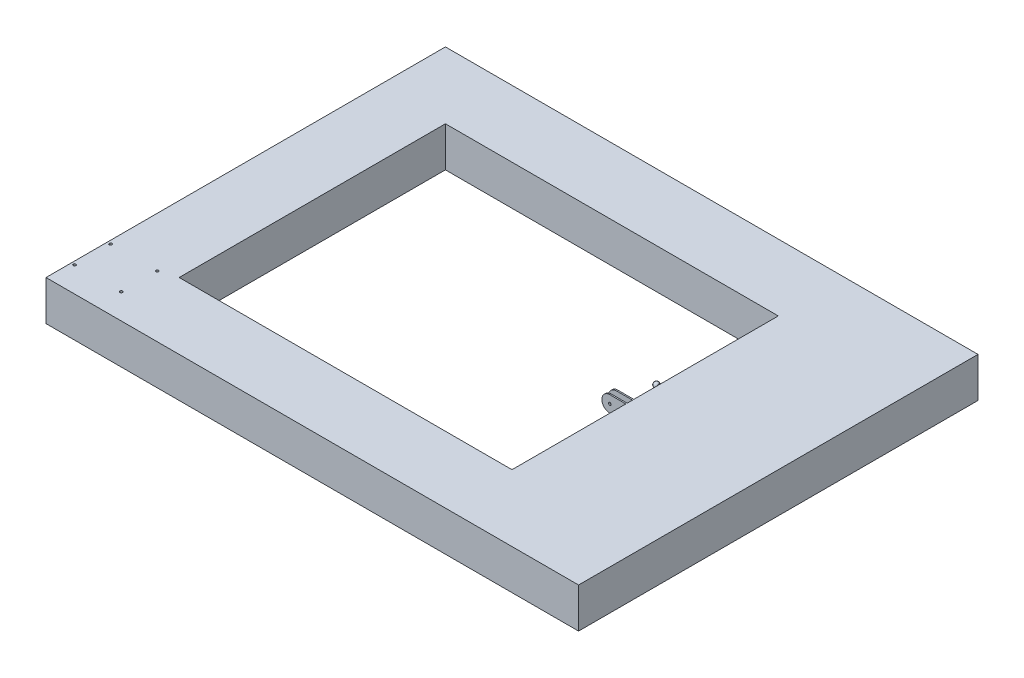
SolidWorks part; units mm, degrees
ref_plane "Front Plane" through (0, 0, 0) normal (0, 0, 1) x (1, 0, 0)
ref_plane "Top Plane" through (0, 0, 0) normal (0, 1, 0) x (1, 0, 0)
ref_plane "Right Plane" through (0, 0, 0) normal (1, 0, 0) x (0, 0, -1)
sketch "Sketch1" plane through (0, 0, 0) normal (0, 0, 1) x (1, 0, 0)
  line L1 (0, 0) -> (4000, 0)
  line L2 (0, 0) -> (0, 300)
  line L3 (0, 300) -> (4000, 300)
  line L4 (4000, 0) -> (4000, 300)
  dimension "D1" = 4000
  dimension "D2" = 300
extrude "Boss-Extrude1" add sketch "Sketch1" along normal blind 3000
sketch "Sketch3" plane through (0, 300, 0) normal (0, 1, 0) x (1, 0, 0)
  line L0 (0, -3000) -> (0, 0) construction
  line L1 (500, -500) -> (3000, -500)
  line L2 (500, -500) -> (500, -2500)
  line L3 (500, -2500) -> (3000, -2500)
  line L4 (3000, -500) -> (3000, -2500)
  line L5 (4000, -3000) -> (0, -3000) construction
  dimension "D1" = 2000
  dimension "D2" = 2500
  dimension "D3" = 500
  dimension "D4" = 500
extrude "Cut-Extrude1" cut sketch "Sketch3" against normal blind 3000
ref_plane "Plane2" through (0, 0, 1645) normal (0, 0, -1) x (-1, 0, 0)
sketch "Sketch6" plane through (0, 0, 1645) normal (0, 0, -1) x (-1, 0, 0)
  line L0 (-3000, 300) -> (-3000, 180)
  line L1 (-3000, 180) -> (-2880, 180)
  line L2 (-2880, 300) -> (-3000, 300)
  arc A0 (-2880, 180) -> (-2880, 300) centre (-2880, 240) ccw
  circle A1 centre (-2880, 240) radius 10
  dimension "D3" = 20
  dimension "D1" = 120
  dimension "D2" = 120
extrude "Boss-Extrude2" add sketch "Sketch6" along normal blind 10
ref_plane "Plane3" through (0, 0, 1595) normal (0, 0, -1) x (-1, 0, 0)
sketch "Sketch7" plane through (0, 0, 1595) normal (0, 0, -1) x (-1, 0, 0)
  line L0 (-3000, 300) -> (-3000, 180) construction
  line L1 (-3000, 180) -> (-2880, 180) construction
  line L2 (-2880, 300) -> (-3000, 300) construction
  line L3 (-3000, 300) -> (-3000, 180)
  line L4 (-3000, 180) -> (-2880, 180)
  line L5 (-2880, 300) -> (-3000, 300)
  circle A0 centre (-2880, 240) radius 10 construction
  arc A1 (-2880, 180) -> (-2880, 300) centre (-2880, 240) ccw construction
  circle A2 centre (-2880, 240) radius 10
  arc A3 (-2880, 180) -> (-2880, 300) centre (-2880, 240) ccw
extrude "Boss-Extrude3" add sketch "Sketch7" along normal blind 10
ref_plane "Plane4" through (0, 0, 1385) normal (0, 0, -1) x (-1, 0, 0)
sketch "Sketch8" plane through (0, 0, 1385) normal (0, 0, -1) x (-1, 0, 0)
  line L0 (-3000, 300) -> (-3000, 280)
  line L2 (-2986.0433, 291.9421) -> (-3000, 300)
  line L3 (-3000, 280) -> (-2950, 280)
  arc A0 (-2950, 280) -> (-2986.0433, 291.9421) centre (-2970, 280) ccw
  dimension "D4" = 20
  dimension "D3" = 50
  dimension "D1" = 60
  dimension "D2" = 20
revolve "Revolve1" add sketch "Sketch8" angle 360 about L3
sketch "Sketch9" plane through (0, 300, 0) normal (0, 1, 0) x (1, 0, 0)
  line L0 (4000, -3000) -> (0, -3000) construction
  line L1 (0, -3000) -> (0, 0) construction
  circle A0 centre (25, -2540) radius 10
  circle A1 centre (375, -2540) radius 10
  circle A2 centre (25, -2810) radius 10
  circle A3 centre (375, -2810) radius 10
  dimension "D1" = 20
  dimension "D2" = 190
  dimension "D3" = 25
  dimension "D4" = 350
  dimension "D5" = 270
extrude "Cut-Extrude2" cut sketch "Sketch9" against normal blind 70
cosmetic thread "Cosmetic Thread1" parameters "D2"=22
cosmetic thread "Cosmetic Thread2" parameters "D2"=22
cosmetic thread "Cosmetic Thread3" parameters "D2"=22
cosmetic thread "Cosmetic Thread4" parameters "D2"=22
